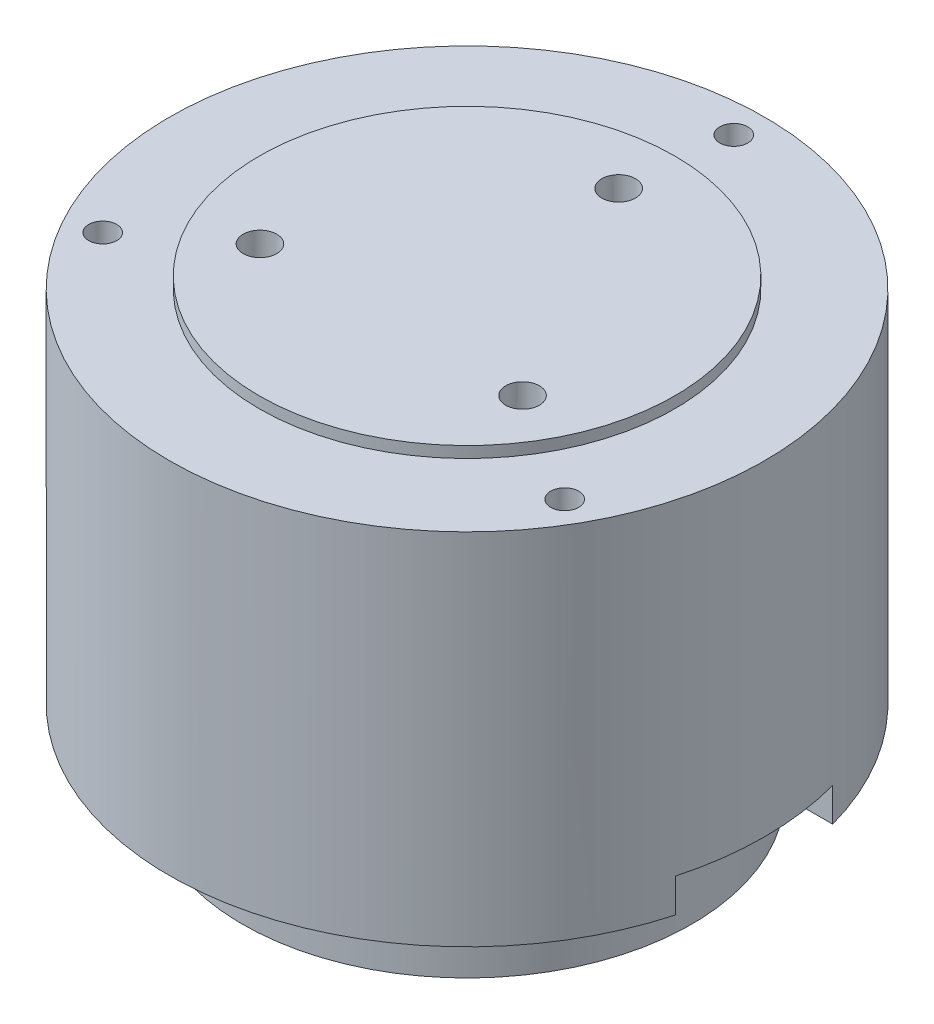
SolidWorks part; units mm, degrees
ref_plane "Front Plane" through (0, 0, 0) normal (0, 0, 1) x (1, 0, 0)
ref_plane "Top Plane" through (0, 0, 0) normal (0, 1, 0) x (1, 0, 0)
ref_plane "Right Plane" through (0, 0, 0) normal (1, 0, 0) x (0, 0, -1)
sketch "Sketch1" plane through (0, 0, 0) normal (0, 1, 0) x (1, 0, 0)
  circle A0 centre (0, 0) radius 26.5
extrude "Boss-Extrude1" add sketch "Sketch1" along normal blind 32
sketch "Sketch2" plane through (0, 0, 0) normal (0, -1, 0) x (1, 0, 0)
  circle A0 centre (0, 0) radius 20
extrude "Boss-Extrude2" add sketch "Sketch2" along normal blind 7
sketch "Sketch3" plane through (0, 32, 0) normal (0, 1, 0) x (1, 0, 0)
  circle A0 centre (0, 0) radius 18.5
extrude "Boss-Extrude3" add sketch "Sketch3" along normal blind 1
sketch "Sketch4" plane through (0, 0, 0) normal (0, -1, 0) x (1, 0, 0)
  circle A0 centre (0, 23.75) radius 1.25
  circle A1 centre (20.5681, 11.875) radius 1.25
  circle A2 centre (20.5681, -11.875) radius 1.25
  circle A3 centre (0, -23.75) radius 1.25
  circle A4 centre (-20.5681, -11.875) radius 1.25
  circle A5 centre (-20.5681, 11.875) radius 1.25
  point P16 (0, 0)
  dimension "D1" = 23.75
  dimension "D2" = 6
extrude "Cut-Extrude1" cut sketch "Sketch4" against normal blind 3
sketch "Sketch5" plane through (0, 33, 0) normal (0, 1, 0) x (1, 0, 0)
  circle A0 centre (0, 13.5) radius 1.5
  circle A1 centre (11.6913, -6.75) radius 1.5
  circle A2 centre (-11.6913, -6.75) radius 1.5
  point P10 (0, 0)
  dimension "D1" = 13.5
  dimension "D2" = 3
extrude "Cut-Extrude2" cut sketch "Sketch5" against normal blind 4
sketch "Sketch6" plane through (0, 32, 0) normal (0, 1, 0) x (1, 0, 0)
  circle A0 centre (0, 23.75) radius 1.25
  circle A1 centre (20.5681, -11.875) radius 1.25
  circle A2 centre (-20.5681, -11.875) radius 1.25
  point P10 (0, 0)
  dimension "D1" = 23.75
  dimension "D2" = 3
extrude "Cut-Extrude3" cut sketch "Sketch6" against normal blind 5
sketch "Sketch7" plane through (0, 0, 0) normal (0, -1, 0) x (1, 0, 0)
  line L1 (-28.911, 7) -> (31.2081, 7)
  line L2 (-28.911, 7) -> (-28.911, -7)
  line L3 (-28.911, -7) -> (31.2081, -7)
  line L4 (31.2081, 7) -> (31.2081, -7)
  dimension "D1" = 14
  dimension "D2" = 7
extrude "Cut-Extrude4" cut sketch "Sketch7" against normal blind 3
